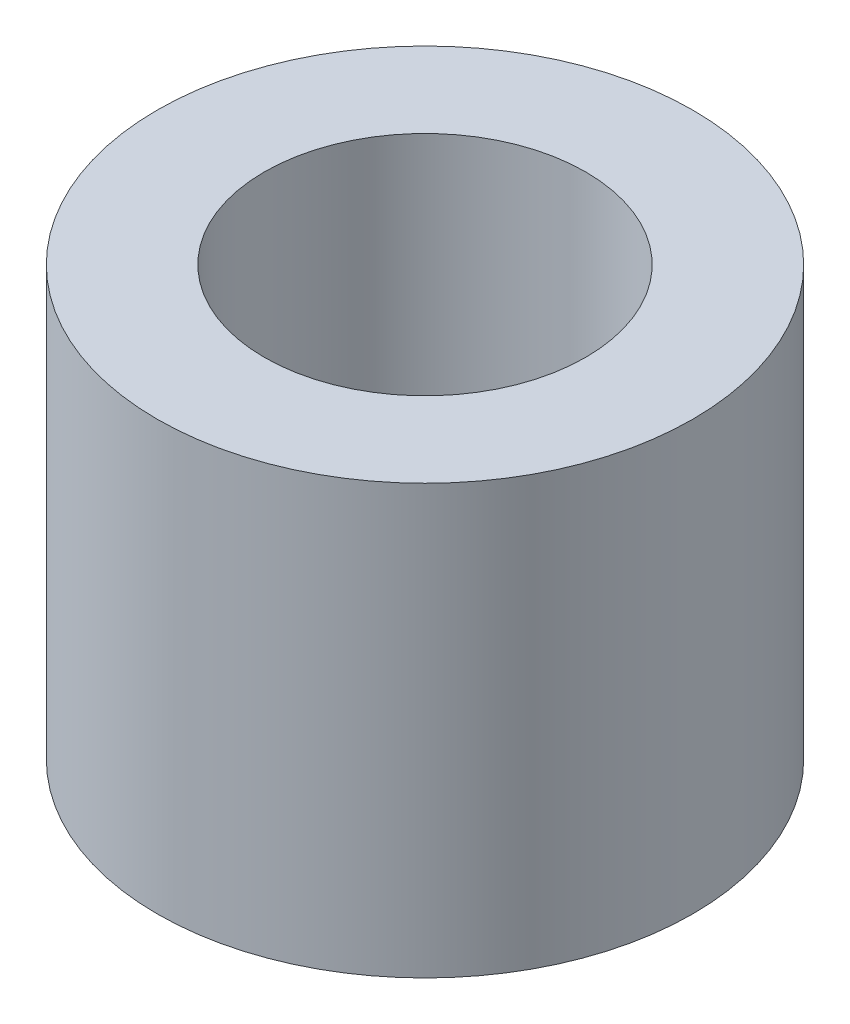
SolidWorks part; units mm, degrees
ref_plane "前视基准面" through (0, 0, 0) normal (0, 0, 1) x (1, 0, 0)
ref_plane "上视基准面" through (0, 0, 0) normal (0, 1, 0) x (1, 0, 0)
ref_plane "右视基准面" through (0, 0, 0) normal (1, 0, 0) x (0, 0, -1)
other "Configuration Table"
sketch "草图1" plane through (0, 0, 0) normal (0, 1, 0) x (1, 0, 0)
  circle A0 centre (0, 0) radius 3
  circle A1 centre (0, 0) radius 5
  dimension "D1" = 6
  dimension "D2" = 10
extrude "凸台-拉伸1" add sketch "草图1" along normal blind 8
